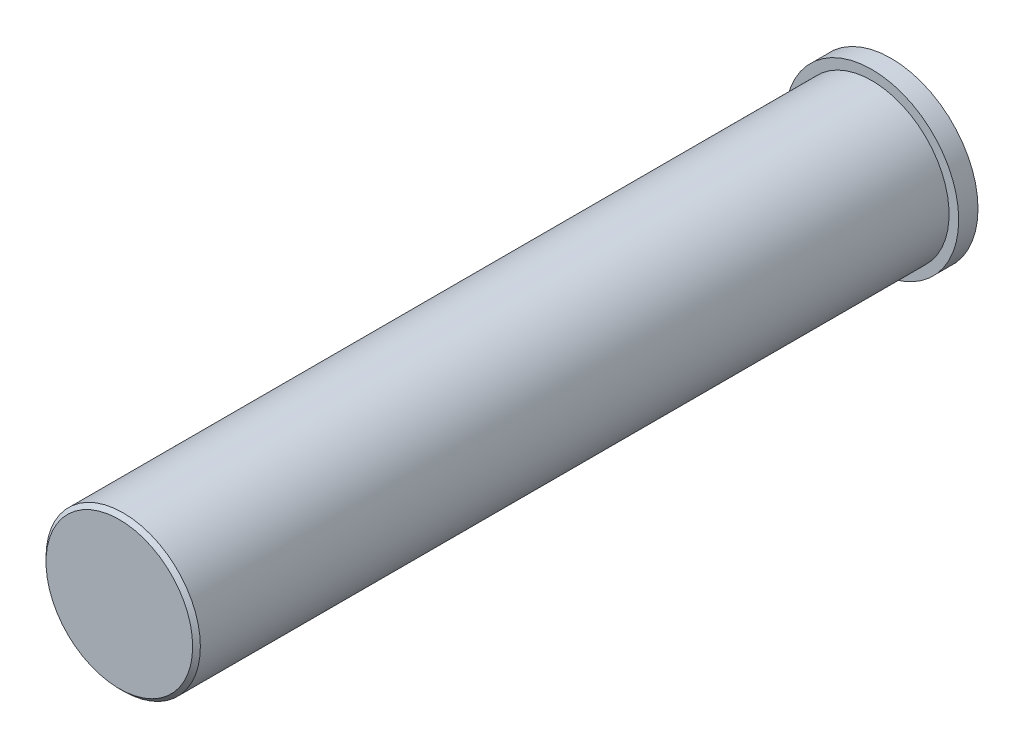
SolidWorks part; units mm, degrees
ref_plane "前视基准面" through (0, 0, 0) normal (0, 0, 1) x (1, 0, 0)
ref_plane "上视基准面" through (0, 0, 0) normal (0, 1, 0) x (1, 0, 0)
ref_plane "右视基准面" through (0, 0, 0) normal (1, 0, 0) x (0, 0, -1)
sketch "草图1" plane through (0, 0, 0) normal (0, 0, 1) x (1, 0, 0)
  circle A0 centre (0, 0) radius 2
  dimension "D1" = 4
extrude "凸台-拉伸1" add sketch "草图1" along normal blind 20
sketch "草图2" plane through (0, 0, 0) normal (0, 0, -1) x (-1, 0, 0)
  circle A0 centre (0, 0) radius 2.25
  dimension "D1" = 4.5
extrude "凸台-拉伸2" add sketch "草图2" against normal blind 0.5
sketch "草图3" plane through (0, 0, 0) normal (0, 0, -1) x (-1, 0, 0)
  circle A0 centre (0, 0) radius 1.5
  dimension "D1" = 3
extrude "切除-拉伸1" cut sketch "草图3" against normal blind 8
chamfer "倒角1" distance 0.1 angle 45 1 edges at (2, 0, 20)
